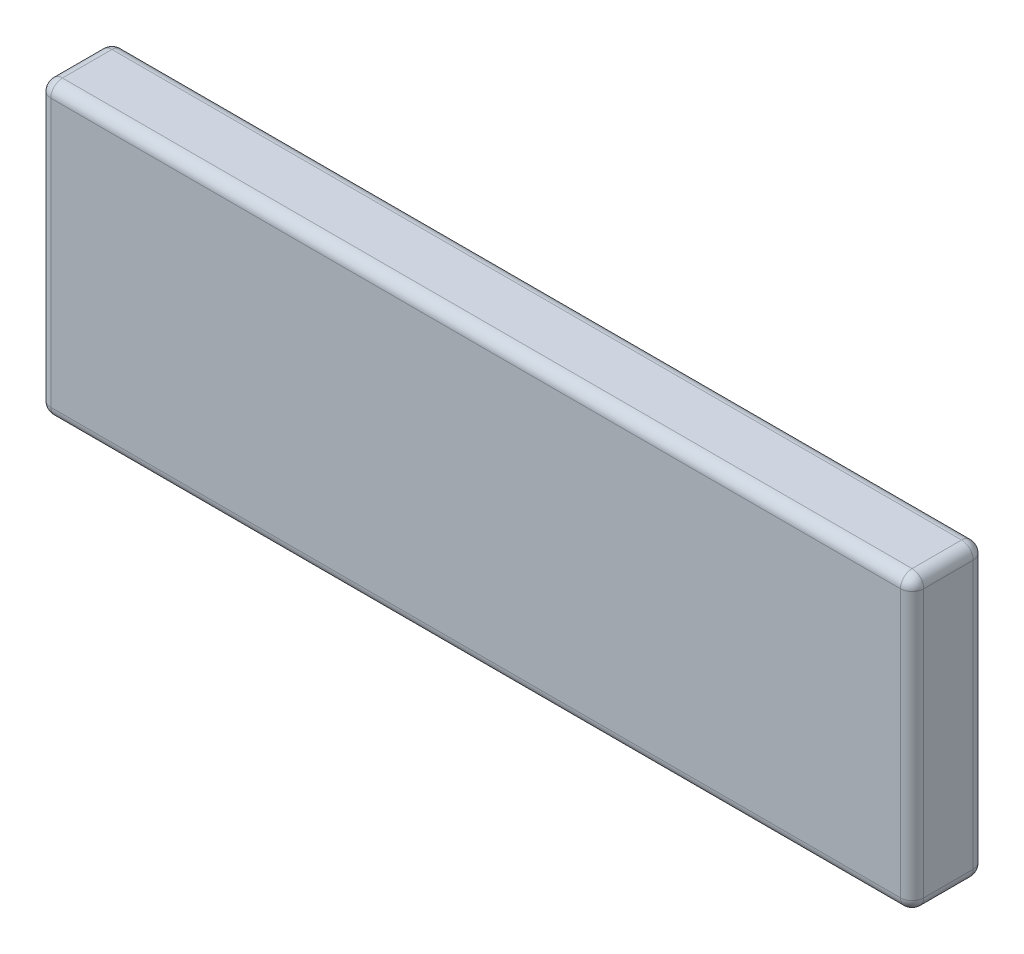
SolidWorks part; units mm, degrees
ref_plane "Front Plane" through (0, 0, 0) normal (0, 0, 1) x (1, 0, 0)
ref_plane "Top Plane" through (0, 0, 0) normal (0, 1, 0) x (1, 0, 0)
ref_plane "Right Plane" through (0, 0, 0) normal (1, 0, 0) x (0, 0, -1)
sketch "Sketch1" plane through (0, 0, 0) normal (0, 0, 1) x (1, 0, 0)
  line L1 (-9.525, -3.175) -> (9.525, -3.175)
  line L2 (-9.525, -3.175) -> (-9.525, 3.175)
  line L3 (-9.525, 3.175) -> (9.525, 3.175)
  line L4 (9.525, -3.175) -> (9.525, 3.175)
  line L5 (-9.525, -3.175) -> (9.525, 3.175) construction
  line L6 (-9.525, 3.175) -> (9.525, -3.175) construction
  point P0 (0, 0)
  dimension "D1" = 6.35
  dimension "D2" = 19.05
extrude "Boss-Extrude1" add sketch "Sketch1" along normal blind 1.5875
fillet "Fillet1" radius 0.254 12 edges at (-9.525, 0, 1.5875) (-9.525, 0, 0) (-9.525, -3.175, 0.7937) (0, -3.175, 1.5875) (0, -3.175, 0) (9.525, -3.175, 0.7937) (9.525, 0, 1.5875) (9.525, 0, 0) (9.525, 3.175, 0.7937) (0, 3.175, 1.5875) (-9.525, 3.175, 0.7937) (0, 3.175, 0)
ref_plane "Plane1" through (0, 0, 1.3335) normal (0, 0, -1) x (-1, 0, 0)
